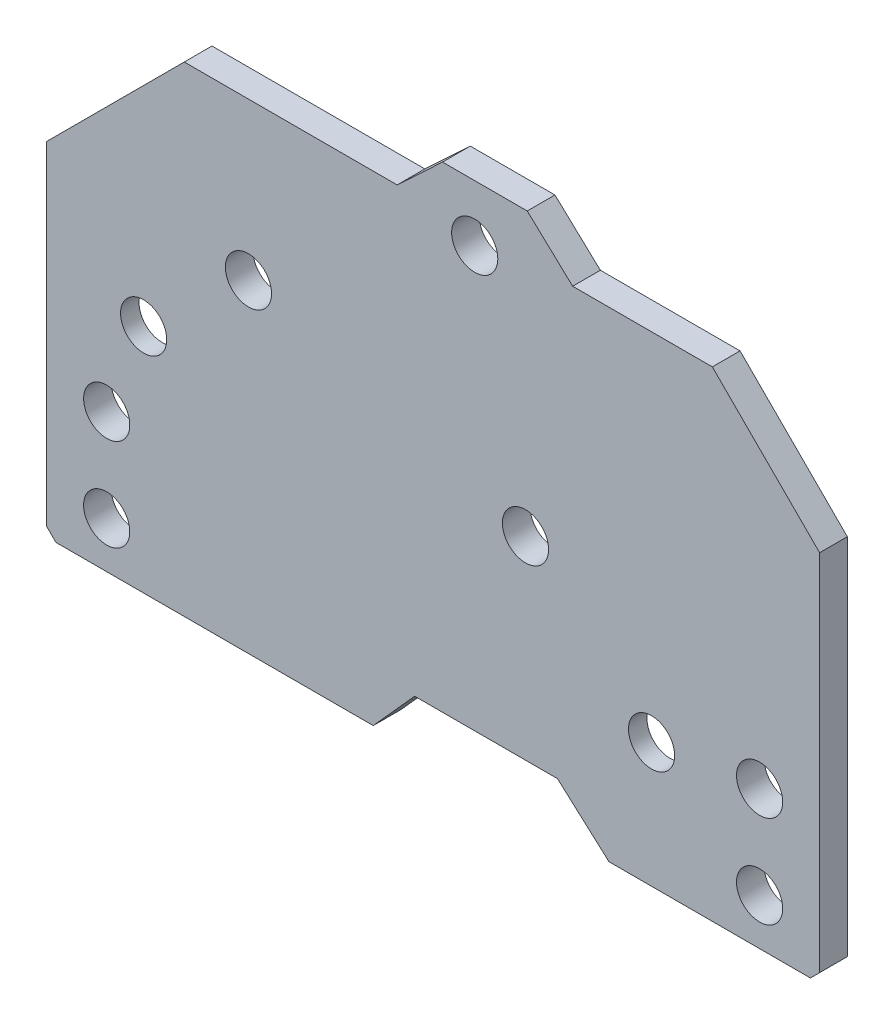
SolidWorks part; units mm, degrees
ref_plane "정면" through (0, 0, 0) normal (0, 0, 1) x (1, 0, 0)
ref_plane "윗면" through (0, 0, 0) normal (0, 1, 0) x (1, 0, 0)
ref_plane "우측면" through (0, 0, 0) normal (1, 0, 0) x (0, 0, -1)
sketch "스케치1" plane through (0, 0, 0) normal (0, 0, 1) x (1, 0, 0)
  line L0 (-7.6862, -28.1969) -> (-3.2005, -23.1969)
  line L1 (-0.1807, 28.4031) -> (8.9903, 28.4031)
  line L2 (-43.0492, 8.9033) -> (-43.0492, -28.1969)
  line L3 (-43.0492, -28.1969) -> (-7.6862, -28.1969)
  line L4 (40.6497, 12.1842) -> (40.6497, -28.1969)
  line L5 (-3.2005, -23.1969) -> (12.2631, -23.1969)
  line L6 (12.2631, -23.1969) -> (17.8363, -28.1969)
  line L7 (17.8363, -28.1969) -> (40.6497, -28.1969)
  line L8 (-28.1493, 23.8031) -> (-43.0492, 8.9033)
  line L9 (29.0307, 23.8031) -> (40.6497, 12.1842)
  line L10 (-0.1807, 28.4031) -> (-5.0966, 23.8031)
  line L11 (-5.0966, 23.8031) -> (-28.1493, 23.8031)
  line L12 (8.9903, 28.4031) -> (13.9062, 23.8031)
  line L13 (13.9062, 23.8031) -> (29.0307, 23.8031)
  circle A0 centre (-21.1998, 6.8031) radius 2.5
  circle A1 centre (3.3002, 22.3031) radius 2.5
  circle A2 centre (8.8002, -2.1969) radius 2.5
  circle A3 centre (-32.5492, -3.1969) radius 5.2
  circle A4 centre (-32.5492, -3.1969) radius 2.5
  circle A5 centre (22.4497, -14.6969) radius 5.2
  circle A6 centre (22.4497, -14.6969) radius 2.5
  point P0 (-1.1998, -0.6969)
  dimension "D1" = 5
  dimension "D2" = 5
  dimension "D3" = 5
  dimension "D9" = 5
  dimension "D10" = 10.4
  dimension "D11" = 5
  dimension "D12" = 10.4
  dimension "D13" = 10.5
  dimension "D4" = 24.5
  dimension "D5" = 24.5
  dimension "D6" = 30
  dimension "D7" = 15.5
  dimension "D8" = 9
  dimension "D14" = 25
  dimension "D15" = 18.2
  dimension "D16" = 13.5
  dimension "D17" = 5
  dimension "D18" = 52
  dimension "D19" = 4.6
extrude "보스-돌출1" add sketch "스케치1" along normal blind 3 contours L13 L12 L1 L10 L11 L8 L2 L3 L0 L5 L6 L7 L4 L9 A5 A3 A2 A1 A0
sketch "스케치3" plane through (0, 0, 3) normal (0, 0, 1) x (1, 0, 0)
  circle A0 centre (-32.5492, -3.1969) radius 5.2 construction
  circle A1 centre (-32.5492, -3.1969) radius 5.2
  circle A2 centre (-32.5492, -3.1969) radius 2.5
  circle A3 centre (22.4497, -14.6969) radius 5.2 construction
  circle A4 centre (22.4497, -14.6969) radius 5.2
  circle A5 centre (22.4497, -14.6969) radius 2.5
  dimension "D1" = 5
  dimension "D2" = 5
extrude "보스-돌출3" add sketch "스케치3" against normal blind 2
sketch "스케치6" plane through (0, 0, 3) normal (0, 0, 1) x (1, 0, 0)
  line L0 (29.9053, 6.8706) -> (36.3941, 6.8706) construction
  line L1 (37.3941, 7.8706) -> (37.3941, 14.3594) construction
  line L2 (36.3941, 15.3594) -> (33.1497, 15.3594) construction
  line L3 (28.9053, 7.8706) -> (28.9053, 11.115) construction
  line L4 (40.6497, 12.1842) -> (40.6497, -28.1969) construction
  line L5 (17.8363, -28.1969) -> (40.6497, -28.1969) construction
  arc A0 (33.1497, 15.3594) -> (28.9053, 11.115) centre (33.1497, 11.115) ccw construction
  arc A1 (29.9053, 6.8706) -> (28.9053, 7.8706) centre (29.9053, 7.8706) cw construction
  arc A2 (36.3941, 6.8706) -> (37.3941, 7.8706) centre (36.3941, 7.8706) ccw construction
  arc A3 (37.3941, 14.3594) -> (36.3941, 15.3594) centre (36.3941, 14.3594) ccw construction
  dimension "D1" = 1
  dimension "D2" = 7.5
  dimension "D3" = 39.3119
sketch "스케치7" plane through (0, 0, 0) normal (0, 0, -1) x (-1, 0, 0)
  line L0 (-37.3941, 7.8706) -> (-37.3941, 14.3594) construction
  line L1 (-36.3941, 15.3594) -> (-33.1497, 15.3594) construction
  line L2 (-28.9053, 7.8706) -> (-28.9053, 11.115) construction
  line L3 (-29.9053, 6.8706) -> (-36.3941, 6.8706) construction
  line L4 (-37.3941, 7.8706) -> (-37.3941, 14.3594)
  line L5 (-36.3941, 15.3594) -> (-33.1497, 15.3594)
  line L6 (-28.9053, 7.8706) -> (-28.9053, 11.115)
  line L7 (-29.9053, 6.8706) -> (-36.3941, 6.8706)
  line L14 (-13.9062, 23.8031) -> (-29.0307, 23.8031)
  line L15 (-29.0307, 23.8031) -> (-40.6497, 12.1842)
  line L16 (-40.6497, 12.1842) -> (-40.6497, -28.1969)
  line L17 (-40.6497, -28.1969) -> (-17.8363, -28.1969)
  line L18 (-17.8363, -28.1969) -> (-12.2631, -23.1969)
  line L19 (-12.2631, -23.1969) -> (3.2005, -23.1969)
  line L20 (3.2005, -23.1969) -> (7.6862, -28.1969)
  line L21 (7.6862, -28.1969) -> (43.0492, -28.1969)
  line L22 (43.0492, -28.1969) -> (43.0492, 8.9033)
  line L23 (43.0492, 8.9033) -> (28.1493, 23.8031)
  line L24 (28.1493, 23.8031) -> (5.0966, 23.8031)
  line L25 (5.0966, 23.8031) -> (0.1807, 28.4031)
  line L26 (0.1807, 28.4031) -> (-8.9903, 28.4031)
  line L27 (-8.9903, 28.4031) -> (-13.9062, 23.8031)
  line L28 (-13.9062, 23.8031) -> (-29.0307, 23.8031)
  line L29 (-29.0307, 23.8031) -> (-40.6497, 12.1842)
  line L30 (-40.6497, 12.1842) -> (-40.6497, -28.1969)
  line L31 (-40.6497, -28.1969) -> (-17.8363, -28.1969)
  line L32 (-17.8363, -28.1969) -> (-12.2631, -23.1969)
  line L33 (-12.2631, -23.1969) -> (3.2005, -23.1969)
  line L34 (3.2005, -23.1969) -> (7.6862, -28.1969)
  line L35 (7.6862, -28.1969) -> (43.0492, -28.1969)
  line L36 (43.0492, -28.1969) -> (43.0492, 8.9033)
  line L37 (43.0492, 8.9033) -> (28.1493, 23.8031)
  line L38 (28.1493, 23.8031) -> (5.0966, 23.8031)
  line L39 (5.0966, 23.8031) -> (0.1807, 28.4031)
  line L40 (0.1807, 28.4031) -> (-8.9903, 28.4031)
  line L41 (-8.9903, 28.4031) -> (-13.9062, 23.8031)
  arc A0 (-36.3941, 15.3594) -> (-37.3941, 14.3594) centre (-36.3941, 14.3594) ccw construction
  arc A1 (-28.9053, 11.115) -> (-33.1497, 15.3594) centre (-33.1497, 11.115) ccw construction
  arc A2 (-29.9053, 6.8706) -> (-28.9053, 7.8706) centre (-29.9053, 7.8706) ccw construction
  arc A3 (-37.3941, 7.8706) -> (-36.3941, 6.8706) centre (-36.3941, 7.8706) ccw construction
  arc A4 (-36.3941, 15.3594) -> (-37.3941, 14.3594) centre (-36.3941, 14.3594) ccw
  arc A5 (-28.9053, 11.115) -> (-33.1497, 15.3594) centre (-33.1497, 11.115) ccw
  arc A6 (-29.9053, 6.8706) -> (-28.9053, 7.8706) centre (-29.9053, 7.8706) ccw
  arc A7 (-37.3941, 7.8706) -> (-36.3941, 6.8706) centre (-36.3941, 7.8706) ccw
  circle A8 centre (8.0492, -24.1969) radius 2.5
  circle A9 centre (6.1493, 21.2031) radius 2.5
  dimension "D2" = 5
  dimension "D5" = 5
  dimension "D3" = 4
  dimension "D4" = 35
  dimension "D6" = 2.6
  dimension "D7" = 22
  dimension "D1" = 0
extrude "컷-돌출1" cut sketch "스케치7" against normal blind 1 contours A8 | A9 | L4 A4 L5 A5 L6 A6 L7 A7
sketch "스케치9" plane through (0, 0, 0) normal (0, 0, -1) x (-1, 0, 0)
  line L1 (-40.6497, -28.1969) -> (-28.1497, -28.1969)
  line L2 (-40.6497, -28.1969) -> (-40.6497, -8.6969)
  line L3 (-40.6497, -8.6969) -> (-28.1497, -8.6969)
  line L4 (-28.1497, -28.1969) -> (-28.1497, -8.6969)
  line L5 (43.0492, -28.1969) -> (30.5492, -28.1969)
  line L6 (43.0492, -28.1969) -> (43.0492, -8.6969)
  line L7 (43.0492, -8.6969) -> (30.5492, -8.6969)
  line L8 (30.5492, -28.1969) -> (30.5492, -8.6969)
  circle A0 centre (-34.1497, -13.1969) radius 2.5
  circle A1 centre (-34.1497, -23.1969) radius 2.5
  circle A2 centre (36.5492, -13.1969) radius 2.5
  circle A3 centre (36.5492, -23.1969) radius 2.5
  dimension "D5" = 5
  dimension "D6" = 5
  dimension "D7" = 5
  dimension "D8" = 5
  dimension "D9" = 5
  dimension "D1" = 12.5
  dimension "D2" = 19.5
  dimension "D3" = 12.5
  dimension "D4" = 19.5
  dimension "D10" = 10
  dimension "D11" = 5
  dimension "D12" = 10
extrude "컷-돌출2" cut sketch "스케치9" against normal up to next contours A0 | A1 | A2 | A3
chamfer "모따기1" distance 1 angle 45 2 edges at (-43.0492, -28.1969, 1.5) (40.6497, -28.1969, 1.5)
